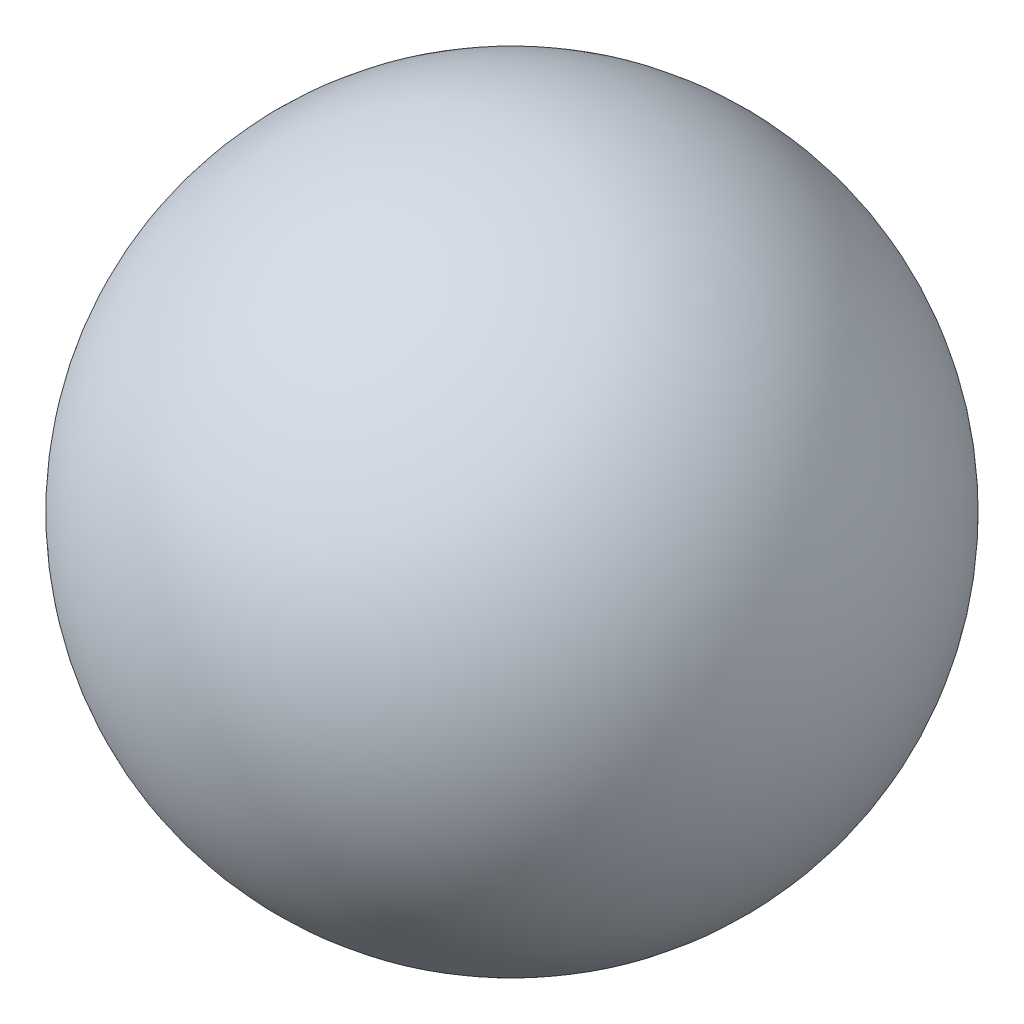
SolidWorks part; units mm, degrees
ref_plane "前视基准面" through (0, 0, 0) normal (0, 0, 1) x (1, 0, 0)
ref_plane "上视基准面" through (0, 0, 0) normal (0, 1, 0) x (1, 0, 0)
ref_plane "右视基准面" through (0, 0, 0) normal (1, 0, 0) x (0, 0, -1)
other "Configuration Table"
sketch "草图1" plane through (0, 0, 0) normal (0, 0, 1) x (1, 0, 0)
  line L0 (0, 0) -> (0, 17)
  arc A0 (0, 17) -> (0, 0) centre (0, 8.5) ccw
  dimension "D1" = 17
revolve "旋转1" add sketch "草图1" angle 360 about L0
